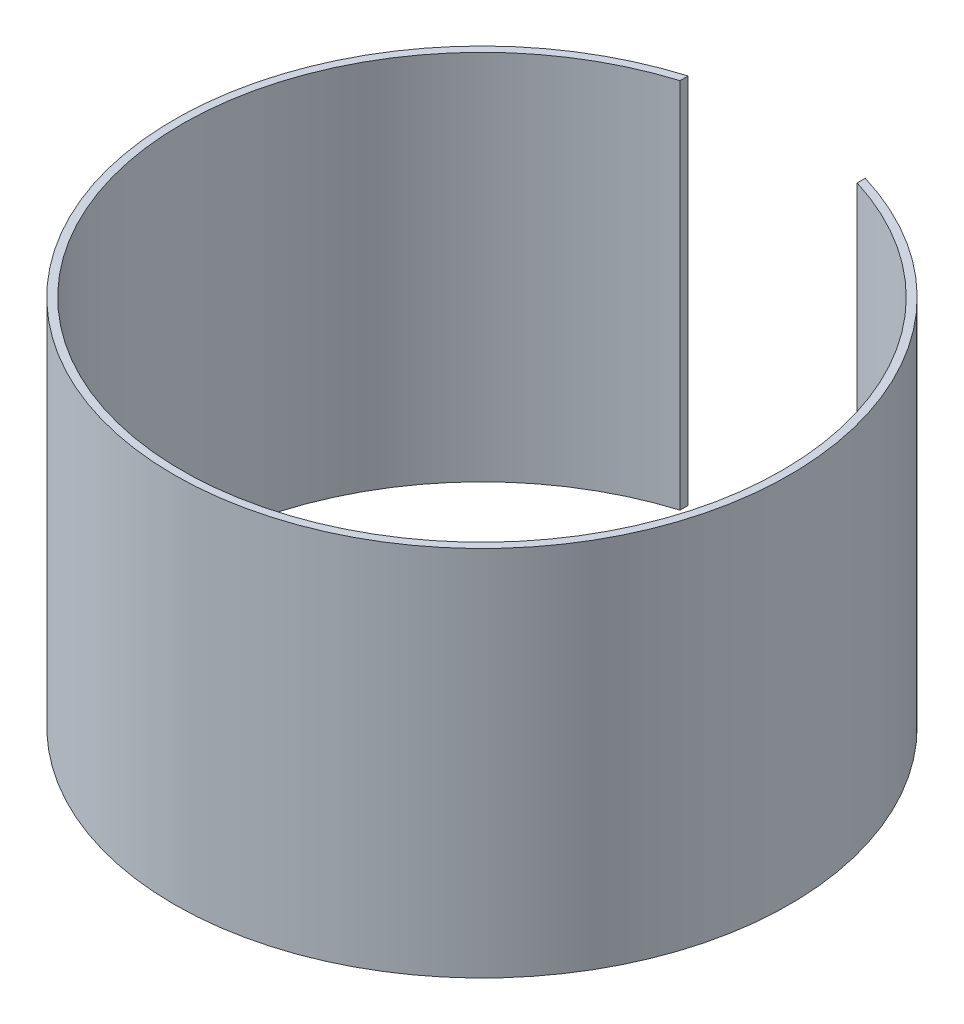
SolidWorks part; units mm, degrees
material "PTFE (general)"
ref_plane "Front Plane" through (0, 0, 0) normal (0, 0, 1) x (1, 0, 0)
ref_plane "Top Plane" through (0, 0, 0) normal (0, 1, 0) x (1, 0, 0)
ref_plane "Right Plane" through (0, 0, 0) normal (1, 0, 0) x (0, 0, -1)
sketch "Sketch1" plane through (0, 0, 0) normal (0, 1, 0) x (1, 0, -0.0097)
  circle A3 centre (-29.3916, 2.6114) radius 40.538
  circle A15 centre (-29.3916, 2.6114) radius 39.522
  dimension "D2" = 79.044
  dimension "D1" = 1.016
extrude "Boss-Extrude1" add sketch "Sketch1" along normal blind 49
sketch "Sketch2" plane through (0, 0, 0) normal (0, 0, 1) x (1, 0, 0)
  line L1 (-17.7495, 19.5) -> (-17.7495, 49)
  line L2 (10.1065, 49) -> (-68.9375, 49) construction
  line L3 (-17.7495, 49) -> (-41.0815, 49)
  line L4 (-41.0815, 49) -> (-41.0815, 0)
  line L5 (-41.0815, 0) -> (-17.7495, 0)
  line L6 (-17.7495, 0) -> (-17.7495, 19.5)
extrude "Cut-Extrude1" cut sketch "Sketch2" against normal blind 48
